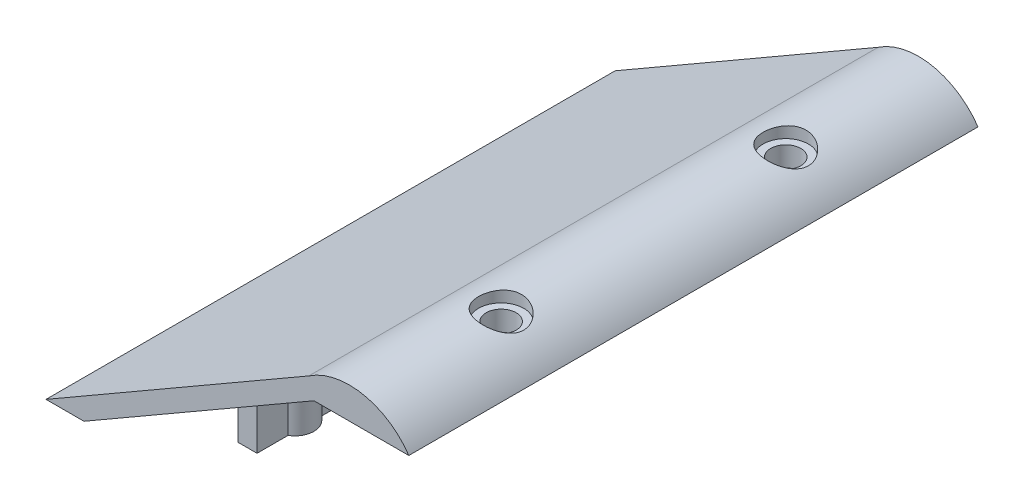
SolidWorks part; units mm, degrees
ref_plane "Alzado" through (0, 0, 0) normal (0, 0, 1) x (1, 0, 0)
ref_plane "Planta" through (0, 0, 0) normal (0, 1, 0) x (1, 0, 0)
ref_plane "Vista lateral" through (0, 0, 0) normal (1, 0, 0) x (0, 0, -1)
sketch "Croquis1" plane through (0, 0, 0) normal (0, 0, 1) x (1, 0, 0)
  line L8 (0, 19.3774) -> (0, -19.3774) construction
  line L9 (-23.0397, 0) -> (25, 0) construction
  line L26 (0, 0) -> (25, 0)
  line L31 (25, 0) -> (25, 5) construction
  line L32 (25, 5) -> (-1.3397, 5) construction
  line L33 (-1.3397, 5) -> (-70.6218, -35)
  line L34 (-70.6218, -35) -> (-60.6218, -35)
  line L35 (-60.6218, -35) -> (0, 0)
  line L38 (-61.6213, -35) -> (53.3616, -35) construction
  line L39 (46.4656, -26) -> (-14.2509, -26) construction
  line L40 (-65.4631, -56) -> (61.4897, -56) construction
  line L41 (0, 0) -> (25, 0) construction
  line L42 (0, 0) -> (25, 0)
  line L43 (0, 0) -> (25, 0)
  arc A0 (-1.3397, 5) -> (25, 0) centre (9.319, -10.7287) cw
  dimension "D6" = 19
  dimension "D1" = 26
  dimension "D2" = 30
  dimension "D3" = 25
  dimension "D4" = 35
  dimension "D5" = 30
  dimension "D7" = 5
  dimension "D8" = 5
extrude "Saliente-Extruir2" add sketch "Croquis1" along normal mid plane 150 contours A0 L33 L34 L35 L26
ref_plane "Plano1" through (0, -15, 0) normal (0, 1, 0) x (1, 0, 0)
sketch "Croquis3" plane through (0, -15, 0) normal (0, -1, 0) x (1, 0, 0)
  line L0 (44.4593, 0) -> (-104.4593, 0) construction
  line L1 (0, 52.1261) -> (0, -47.2849) construction
  line L2 (0, 75) -> (0, -75) construction
  line L3 (-30, 99.6856) -> (-30, -100.7612) construction
  line L4 (-32.5, 4.3301) -> (-32.5, 12.5)
  line L5 (-32.5, -12.5) -> (-27.5, -12.5)
  line L6 (-32.5, -12.5) -> (-32.5, -4.3301)
  line L7 (-32.5, 12.5) -> (-27.5, 12.5)
  line L8 (-27.5, -12.5) -> (-27.5, -4.3301)
  line L9 (-32.5, -12.5) -> (-27.5, 12.5) construction
  line L10 (-32.5, 12.5) -> (-27.5, -12.5) construction
  line L11 (-27.5, 4.3301) -> (-27.5, 12.5)
  line L12 (-27.5, -45.6699) -> (-27.5, -37.5)
  line L13 (-32.5, -37.5) -> (-27.5, -37.5)
  line L14 (-32.5, -45.6699) -> (-32.5, -37.5)
  line L15 (-32.5, -62.5) -> (-32.5, -54.3301)
  line L16 (-32.5, -62.5) -> (-27.5, -62.5)
  line L17 (-27.5, -62.5) -> (-27.5, -54.3301)
  line L18 (-27.5, 4.3301) -> (-27.5, -45.6699) construction
  line L19 (-27.5, 54.3301) -> (-27.5, 62.5)
  line L20 (-32.5, 62.5) -> (-27.5, 62.5)
  line L21 (-32.5, 54.3301) -> (-32.5, 62.5)
  line L22 (-32.5, 37.5) -> (-32.5, 45.6699)
  line L23 (-32.5, 37.5) -> (-27.5, 37.5)
  line L24 (-27.5, 37.5) -> (-27.5, 45.6699)
  line L25 (-27.5, 4.3301) -> (-27.5, 54.3301) construction
  arc A0 (-32.5, 4.3301) -> (-32.5, -4.3301) centre (-30, 0) ccw
  arc A1 (-32.5, -45.6699) -> (-32.5, -54.3301) centre (-30, -50) ccw
  arc A2 (-27.5, -4.3301) -> (-27.5, 4.3301) centre (-30, 0) ccw
  arc A3 (-27.5, -54.3301) -> (-27.5, -45.6699) centre (-30, -50) ccw
  arc A4 (-32.5, 54.3301) -> (-32.5, 45.6699) centre (-30, 50) ccw
  arc A5 (-27.5, 45.6699) -> (-27.5, 54.3301) centre (-30, 50) ccw
  dimension "D1" = 10
  dimension "D2" = 30
  dimension "D3" = 5
  dimension "D4" = 25
  dimension "D6" = 50
  dimension "D8" = 50
  dimension "D5" = 2
  dimension "D7" = 2
extrude "Saliente-Extruir5" add sketch "Croquis3" along normal blind 17 and the other way up to surface other way up to face at (-30.3109, -17.5, 0)
ref_plane "Plano3" through (0, 8.2713, 0) normal (0, 1, 0) x (1, 0, 0)
sketch "Croquis6" plane through (0, 8.2713, 0) normal (0, 1, 0) x (1, 0, 0)
  line L0 (55.4332, 0) -> (-96.6388, 0) construction
  line L1 (11.8301, 106.169) -> (11.8301, -106.169) construction
  line L6 (25, 75) -> (-1.3397, 75)
  line L7 (-1.3397, 75) -> (-1.3397, -75)
  line L8 (-1.3397, -75) -> (25, -75)
  line L9 (25, -75) -> (25, 75)
  line L10 (25, 75) -> (-1.3397, 75)
  line L11 (-1.3397, 75) -> (-1.3397, -75)
  line L12 (-1.3397, -75) -> (25, -75)
  line L13 (25, -75) -> (25, 75)
  circle A0 centre (11.8301, 37.5) radius 3.9688
  circle A1 centre (11.8301, -37.5) radius 3.9688
  point P7 (11.8301, 0)
  dimension "D3" = 7.9375
  dimension "D2" = 11.8301
  dimension "D4" = 37.5
  dimension "D1" = 0
extrude "Cortar-Extruir2" cut sketch "Croquis6" against normal blind 20 contours A1 | A0
sketch "Croquis16" plane through (0, 8.2713, 0) normal (0, 1, 0) x (1, 0, 0)
  circle A0 centre (11.8301, -37.5) radius 3.9688 construction
  circle A1 centre (11.8301, 37.5) radius 3.9688 construction
  circle A2 centre (11.8301, -37.5) radius 3.9688
  circle A3 centre (11.8301, 37.5) radius 3.9688
  circle A4 centre (11.8301, 37.5) radius 5.9688
  circle A5 centre (11.8301, -37.5) radius 5.9688
  dimension "D1" = 2
extrude "Cortar-Extruir3" cut sketch "Croquis16" against normal blind 3
sketch "Croquis17" plane through (0, -32, 0) normal (0, -1, 0) x (1, 0, 0)
  line L0 (-27.5, -37.5) -> (-32.5, -37.5) construction
  line L1 (-32.5, -37.5) -> (-32.5, -45.6699) construction
  line L2 (-32.5, -54.3301) -> (-32.5, -62.5) construction
  line L3 (-32.5, -62.5) -> (-27.5, -62.5) construction
  line L4 (-27.5, -62.5) -> (-27.5, -54.3301) construction
  line L5 (-27.5, -45.6699) -> (-27.5, -37.5) construction
  line L6 (-27.5, 4.3301) -> (-27.5, 12.5)
  line L7 (-27.5, 12.5) -> (-32.5, 12.5)
  line L8 (-32.5, 12.5) -> (-32.5, 4.3301)
  line L9 (-32.5, -4.3301) -> (-32.5, -12.5)
  line L10 (-32.5, -12.5) -> (-27.5, -12.5)
  line L11 (-27.5, -12.5) -> (-27.5, -4.3301)
  line L12 (-27.5, 4.3301) -> (-27.5, 12.5)
  line L13 (-27.5, 12.5) -> (-32.5, 12.5)
  line L14 (-32.5, 12.5) -> (-32.5, 4.3301)
  line L15 (-32.5, -4.3301) -> (-32.5, -12.5)
  line L16 (-32.5, -12.5) -> (-27.5, -12.5)
  line L17 (-27.5, -12.5) -> (-27.5, -4.3301)
  line L18 (-27.5, 62.5) -> (-32.5, 62.5) construction
  line L19 (-32.5, 62.5) -> (-32.5, 54.3301) construction
  line L20 (-32.5, 45.6699) -> (-32.5, 37.5) construction
  line L21 (-32.5, 37.5) -> (-27.5, 37.5) construction
  line L22 (-27.5, 37.5) -> (-27.5, 45.6699) construction
  line L23 (-27.5, 54.3301) -> (-27.5, 62.5) construction
  line L24 (-27.5, -37.5) -> (-32.5, -37.5)
  line L25 (-32.5, -37.5) -> (-32.5, -45.6699)
  line L26 (-32.5, -54.3301) -> (-32.5, -62.5)
  line L27 (-32.5, -62.5) -> (-27.5, -62.5)
  line L28 (-27.5, -62.5) -> (-27.5, -54.3301)
  line L29 (-27.5, -45.6699) -> (-27.5, -37.5)
  line L30 (-27.5, 62.5) -> (-32.5, 62.5)
  line L31 (-32.5, 62.5) -> (-32.5, 54.3301)
  line L32 (-32.5, 45.6699) -> (-32.5, 37.5)
  line L33 (-32.5, 37.5) -> (-27.5, 37.5)
  line L34 (-27.5, 37.5) -> (-27.5, 45.6699)
  line L35 (-27.5, 54.3301) -> (-27.5, 62.5)
  arc A0 (-32.5, -45.6699) -> (-32.5, -54.3301) centre (-30, -50) ccw construction
  arc A1 (-27.5, -54.3301) -> (-27.5, -45.6699) centre (-30, -50) ccw construction
  arc A2 (-32.5, 4.3301) -> (-32.5, -4.3301) centre (-30, 0) ccw
  arc A3 (-27.5, -4.3301) -> (-27.5, 4.3301) centre (-30, 0) ccw
  arc A4 (-32.5, 4.3301) -> (-32.5, -4.3301) centre (-30, 0) ccw
  arc A5 (-27.5, -4.3301) -> (-27.5, 4.3301) centre (-30, 0) ccw
  arc A6 (-32.5, 54.3301) -> (-32.5, 45.6699) centre (-30, 50) ccw construction
  arc A7 (-27.5, 45.6699) -> (-27.5, 54.3301) centre (-30, 50) ccw construction
  arc A8 (-32.5, -45.6699) -> (-32.5, -54.3301) centre (-30, -50) ccw
  arc A9 (-27.5, -54.3301) -> (-27.5, -45.6699) centre (-30, -50) ccw
  arc A10 (-32.5, 54.3301) -> (-32.5, 45.6699) centre (-30, 50) ccw
  arc A11 (-27.5, 45.6699) -> (-27.5, 54.3301) centre (-30, 50) ccw
  circle A12 centre (-30, 0) radius 1
  circle A13 centre (-30, 50) radius 1
  circle A14 centre (-30, -50) radius 1
  dimension "D2" = 2
  dimension "D1" = 0
extrude "Cortar-Extruir4" cut sketch "Croquis17" against normal blind 13 contours A13 | A12 | A14
sketch "Croquis18" plane through (0, -35, 0) normal (0, -1, 0) x (1, 0, 0)
  line L4 (-70.6218, -75) -> (-60.6218, -75)
  line L5 (-60.6218, -75) -> (-60.6218, 75)
  line L6 (-60.6218, 75) -> (-70.6218, 75)
  line L7 (-70.6218, 75) -> (-70.6218, -75)
  line L8 (-70.6218, -75) -> (-60.6218, -75)
  line L9 (-60.6218, -75) -> (-60.6218, 75)
  line L10 (-60.6218, 75) -> (-70.6218, 75)
  line L11 (-70.6218, 75) -> (-70.6218, -75)
  line L14 (-27.5, -37.5) -> (-32.5, -37.5)
  line L15 (-32.5, -37.5) -> (-32.5, -45.6699)
  line L16 (-32.5, -54.3301) -> (-32.5, -62.5)
  line L17 (-32.5, -62.5) -> (-27.5, -62.5)
  line L18 (-27.5, -62.5) -> (-27.5, -54.3301)
  line L19 (-27.5, -45.6699) -> (-27.5, -37.5)
  line L20 (-27.5, -37.5) -> (-32.5, -37.5)
  line L21 (-32.5, -37.5) -> (-32.5, -45.6699)
  line L22 (-32.5, -54.3301) -> (-32.5, -62.5)
  line L23 (-32.5, -62.5) -> (-27.5, -62.5)
  line L24 (-27.5, -62.5) -> (-27.5, -54.3301)
  line L25 (-27.5, -45.6699) -> (-27.5, -37.5)
  arc A2 (-32.5, -45.6699) -> (-32.5, -54.3301) centre (-30, -50) ccw
  arc A3 (-27.5, -54.3301) -> (-27.5, -45.6699) centre (-30, -50) ccw
  arc A4 (-32.5, -45.6699) -> (-32.5, -54.3301) centre (-30, -50) ccw
  arc A5 (-27.5, -54.3301) -> (-27.5, -45.6699) centre (-30, -50) ccw
  dimension "D1" = 0
  dimension "D2" = 0
